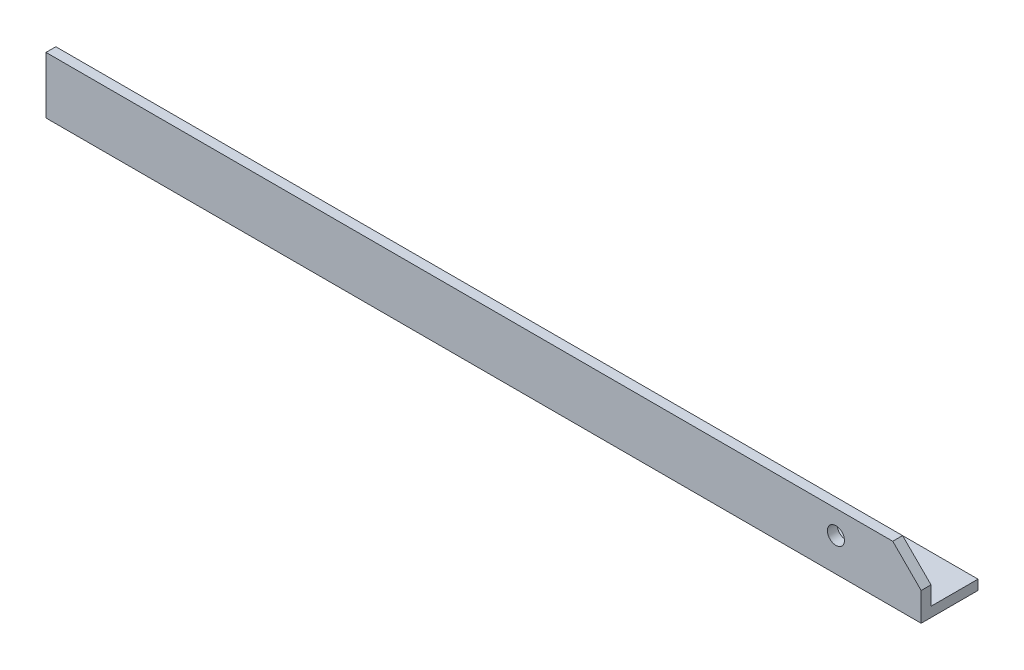
SolidWorks part; units mm, degrees
ref_plane "Front Plane" through (0, 0, 0) normal (0, 0, 1) x (1, 0, 0)
ref_plane "Top Plane" through (0, 0, 0) normal (0, 1, 0) x (1, 0, 0)
ref_plane "Right Plane" through (0, 0, 0) normal (1, 0, 0) x (0, 0, -1)
sketch "Sketch1" plane through (0, 0, 0) normal (1, 0, 0) x (0, 0, -1)
  line L0 (0, 0) -> (20, 0)
  line L1 (20, 0) -> (20, 3.4612)
  line L2 (20, 3.4612) -> (3.4612, 3.4612)
  line L3 (3.4612, 3.4612) -> (3.4612, 20)
  line L4 (3.4612, 20) -> (0, 20)
  line L5 (0, 20) -> (0, 0)
  dimension "D1" = 3.4612
  dimension "D2" = 20
extrude "Boss-Extrude1" add sketch "Sketch1" along normal blind 308
sketch "Sketch2" plane through (0, 0, 0) normal (0, 0, 1) x (1, 0, 0)
  line L0 (308, 20) -> (308, 0) construction
  line L1 (308, 0) -> (0, 0) construction
  line L2 (308, 10) -> (298, 20)
  line L3 (308, 20) -> (0, 20) construction
  line L4 (298, 20) -> (308, 20)
  line L5 (308, 20) -> (308, 10)
  line L10 (243.1149, -13.75) -> (390.1591, -13.75) construction
  circle A0 centre (278, 11.75) radius 3
  dimension "D1" = 6
  dimension "D2" = 30
  dimension "D3" = 25.5
  dimension "D5" = 13.75
  dimension "D4" = 10
extrude "Cut-Extrude1" cut sketch "Sketch2" against normal through all
